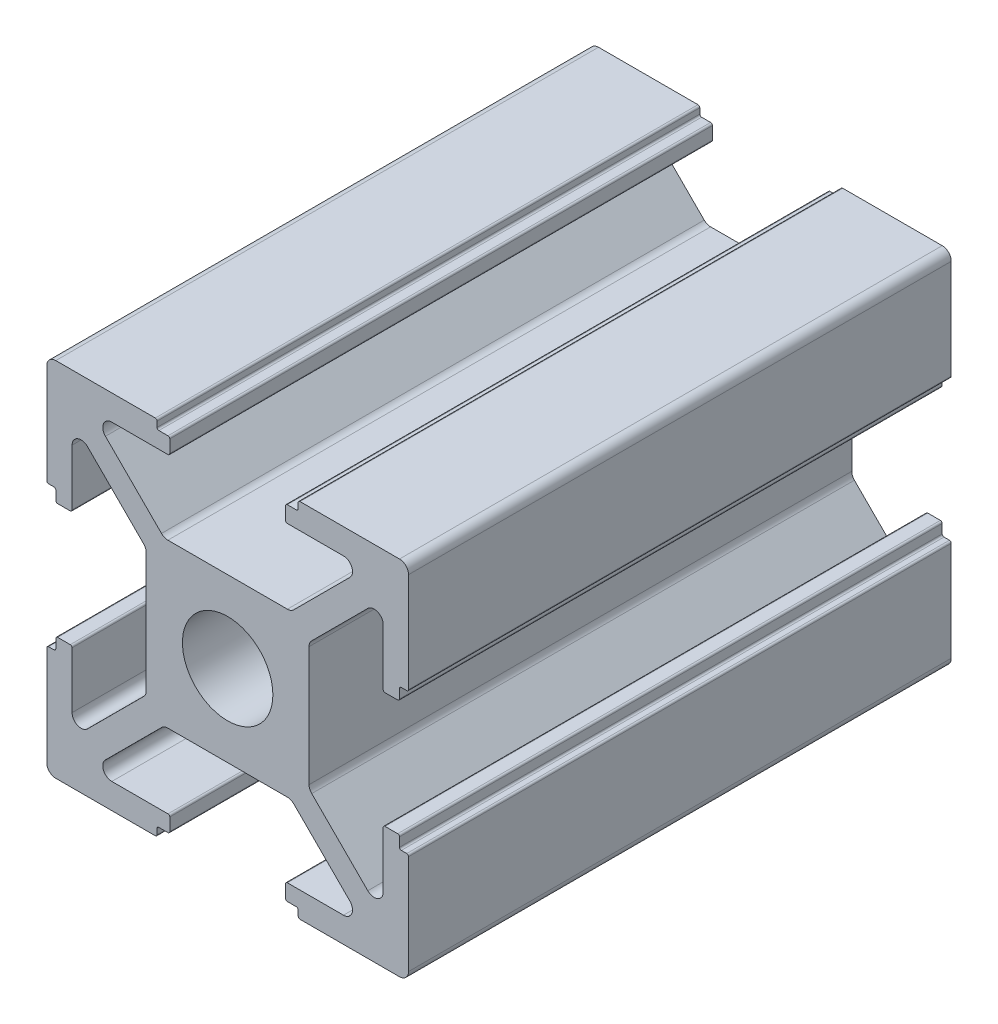
SolidWorks part; units mm, degrees
material "6061 Alaşım"
ref_plane "Ön Düzlem" through (0, 0, 0) normal (0, 0, 1) x (1, 0, 0)
ref_plane "Üst Düzlem" through (0, 0, 0) normal (0, 1, 0) x (1, 0, 0)
ref_plane "Sağ Düzlem" through (0, 0, 0) normal (1, 0, 0) x (0, 0, -1)
sketch "Çizim1" plane through (0, 0, 0) normal (0, 0, 1) x (1, 0, 0)
  line L0 (0, 0) -> (10, 10) construction
  line L1 (10, -10) -> (-10, -10) construction
  line L2 (10, -10) -> (10, 10) construction
  line L3 (10, 10) -> (-10, 10) construction
  line L4 (-10, -10) -> (-10, 10) construction
  line L5 (0, 10) -> (0, -10) construction
  line L6 (10, 0) -> (-10, 0) construction
  line L7 (4.5, 3.5101) -> (10, 9.0101) construction
  line L8 (3.5101, 4.5) -> (9.0101, 10) construction
  line L9 (10, 3.2) -> (8.6, 3.2) construction
  line L10 (8.6, 3.3) -> (8.6, 6.4029)
  line L11 (6.4029, 8.6) -> (3.3, 8.6)
  line L12 (3.2, 8.6) -> (3.2, 10) construction
  line L13 (3.6565, 4.6464) -> (6.7565, 7.7464)
  line L14 (7.7464, 6.7565) -> (4.6464, 3.6565)
  line L15 (3.2, 10) -> (9.5, 10) construction
  line L16 (10, 9.5) -> (10, 3.2) construction
  line L17 (4.5, 3.3029) -> (4.5, 0)
  line L18 (3.3029, 4.5) -> (0, 4.5)
  line L19 (3.3, 9.5) -> (3.8, 9.5)
  line L20 (3.9, 9.6) -> (3.9, 9.9)
  line L21 (3.2, 9.4) -> (3.2, 8.7)
  line L22 (4, 10) -> (9.5, 10)
  line L23 (9.5, 3.3) -> (9.5, 3.8)
  line L24 (9.6, 3.9) -> (9.9, 3.9)
  line L25 (8.7, 3.2) -> (9.4, 3.2)
  line L26 (10, 4) -> (10, 9.5)
  line L27 (0, 0) -> (10, -10) construction
  line L28 (3.3029, -4.5) -> (0, -4.5)
  line L29 (6.7565, -7.7464) -> (3.6565, -4.6464)
  line L30 (3.3, -8.6) -> (6.4029, -8.6)
  line L31 (3.2, -8.7) -> (3.2, -9.4)
  line L32 (3.3, -9.5) -> (3.8, -9.5)
  line L33 (3.9, -9.6) -> (3.9, -9.9)
  line L34 (4, -10) -> (9.5, -10)
  line L35 (10, -4) -> (10, -9.5)
  line L36 (9.6, -3.9) -> (9.9, -3.9)
  line L37 (9.5, -3.3) -> (9.5, -3.8)
  line L38 (9.4, -3.2) -> (8.7, -3.2)
  line L39 (8.6, -6.4029) -> (8.6, -3.3)
  line L40 (4.6464, -3.6565) -> (7.7464, -6.7565)
  line L41 (4.5, -3.3029) -> (4.5, 0)
  line L42 (0, 0) -> (-10, -10) construction
  line L43 (-4.5, -3.3029) -> (-4.5, 0)
  line L44 (-7.7464, -6.7565) -> (-4.6464, -3.6565)
  line L45 (-8.6, -3.3) -> (-8.6, -6.4029)
  line L46 (-8.7, -3.2) -> (-9.4, -3.2)
  line L47 (-9.5, -3.3) -> (-9.5, -3.8)
  line L48 (-9.6, -3.9) -> (-9.9, -3.9)
  line L49 (-10, -4) -> (-10, -9.5)
  line L50 (-4, -10) -> (-9.5, -10)
  line L51 (-3.9, -9.6) -> (-3.9, -9.9)
  line L52 (-3.3, -9.5) -> (-3.8, -9.5)
  line L53 (-3.2, -9.4) -> (-3.2, -8.7)
  line L54 (-6.4029, -8.6) -> (-3.3, -8.6)
  line L55 (-3.6565, -4.6464) -> (-6.7565, -7.7464)
  line L56 (-3.3029, -4.5) -> (0, -4.5)
  line L57 (0, 0) -> (-10, 10) construction
  line L58 (-3.3029, 4.5) -> (0, 4.5)
  line L59 (-6.7565, 7.7464) -> (-3.6565, 4.6464)
  line L60 (-3.3, 8.6) -> (-6.4029, 8.6)
  line L61 (-3.2, 8.7) -> (-3.2, 9.4)
  line L62 (-3.3, 9.5) -> (-3.8, 9.5)
  line L63 (-3.9, 9.6) -> (-3.9, 9.9)
  line L64 (-4, 10) -> (-9.5, 10)
  line L65 (-10, 4) -> (-10, 9.5)
  line L66 (-9.6, 3.9) -> (-9.9, 3.9)
  line L67 (-9.5, 3.3) -> (-9.5, 3.8)
  line L68 (-9.4, 3.2) -> (-8.7, 3.2)
  line L69 (-8.6, 6.4029) -> (-8.6, 3.3)
  line L70 (-4.6464, 3.6565) -> (-7.7464, 6.7565)
  line L71 (-4.5, 3.3029) -> (-4.5, 0)
  circle A0 centre (0, 0) radius 2.5
  arc A1 (10, 9.5) -> (9.5, 10) centre (9.5, 9.5) ccw
  arc A2 (4.5, 3.3029) -> (4.6464, 3.6565) centre (5, 3.3029) cw
  arc A3 (3.6565, 4.6464) -> (3.3029, 4.5) centre (3.3029, 5) cw
  arc A4 (8.6, 6.4029) -> (7.7464, 6.7565) centre (8.1, 6.4029) ccw
  arc A5 (6.4029, 8.6) -> (6.7565, 7.7464) centre (6.4029, 8.1) cw
  arc A6 (9.5, 3.8) -> (9.6, 3.9) centre (9.6, 3.8) cw
  arc A7 (9.9, 3.9) -> (10, 4) centre (9.9, 4) ccw
  arc A8 (8.7, 3.2) -> (8.6, 3.3) centre (8.7, 3.3) cw
  arc A9 (9.5, 3.3) -> (9.4, 3.2) centre (9.4, 3.3) cw
  arc A10 (3.3, 8.6) -> (3.2, 8.7) centre (3.3, 8.7) cw
  arc A11 (3.8, 9.5) -> (3.9, 9.6) centre (3.8, 9.6) ccw
  arc A12 (3.9, 9.9) -> (4, 10) centre (4, 9.9) cw
  arc A13 (3.3, 9.5) -> (3.2, 9.4) centre (3.3, 9.4) ccw
  arc A14 (3.3029, -4.5) -> (3.6565, -4.6464) centre (3.3029, -5) cw
  arc A15 (6.4029, -8.6) -> (6.7565, -7.7464) centre (6.4029, -8.1) ccw
  arc A16 (3.2, -8.7) -> (3.3, -8.6) centre (3.3, -8.7) cw
  arc A17 (3.3, -9.5) -> (3.2, -9.4) centre (3.3, -9.4) cw
  arc A18 (3.8, -9.5) -> (3.9, -9.6) centre (3.8, -9.6) cw
  arc A19 (3.9, -9.9) -> (4, -10) centre (4, -9.9) ccw
  arc A20 (9.5, -10) -> (10, -9.5) centre (9.5, -9.5) ccw
  arc A21 (9.9, -3.9) -> (10, -4) centre (9.9, -4) cw
  arc A22 (9.5, -3.8) -> (9.6, -3.9) centre (9.6, -3.8) ccw
  arc A23 (9.5, -3.3) -> (9.4, -3.2) centre (9.4, -3.3) ccw
  arc A24 (8.6, -3.3) -> (8.7, -3.2) centre (8.7, -3.3) cw
  arc A25 (8.6, -6.4029) -> (7.7464, -6.7565) centre (8.1, -6.4029) cw
  arc A26 (4.6464, -3.6565) -> (4.5, -3.3029) centre (5, -3.3029) cw
  arc A27 (-4.5, -3.3029) -> (-4.6464, -3.6565) centre (-5, -3.3029) cw
  arc A28 (-8.6, -6.4029) -> (-7.7464, -6.7565) centre (-8.1, -6.4029) ccw
  arc A29 (-8.7, -3.2) -> (-8.6, -3.3) centre (-8.7, -3.3) cw
  arc A30 (-9.5, -3.3) -> (-9.4, -3.2) centre (-9.4, -3.3) cw
  arc A31 (-9.5, -3.8) -> (-9.6, -3.9) centre (-9.6, -3.8) cw
  arc A32 (-9.9, -3.9) -> (-10, -4) centre (-9.9, -4) ccw
  arc A33 (-10, -9.5) -> (-9.5, -10) centre (-9.5, -9.5) ccw
  arc A34 (-3.9, -9.9) -> (-4, -10) centre (-4, -9.9) cw
  arc A35 (-3.8, -9.5) -> (-3.9, -9.6) centre (-3.8, -9.6) ccw
  arc A36 (-3.3, -9.5) -> (-3.2, -9.4) centre (-3.3, -9.4) ccw
  arc A37 (-3.3, -8.6) -> (-3.2, -8.7) centre (-3.3, -8.7) cw
  arc A38 (-6.4029, -8.6) -> (-6.7565, -7.7464) centre (-6.4029, -8.1) cw
  arc A39 (-3.6565, -4.6464) -> (-3.3029, -4.5) centre (-3.3029, -5) cw
  arc A40 (-3.3029, 4.5) -> (-3.6565, 4.6464) centre (-3.3029, 5) cw
  arc A41 (-6.4029, 8.6) -> (-6.7565, 7.7464) centre (-6.4029, 8.1) ccw
  arc A42 (-3.2, 8.7) -> (-3.3, 8.6) centre (-3.3, 8.7) cw
  arc A43 (-3.3, 9.5) -> (-3.2, 9.4) centre (-3.3, 9.4) cw
  arc A44 (-3.8, 9.5) -> (-3.9, 9.6) centre (-3.8, 9.6) cw
  arc A45 (-3.9, 9.9) -> (-4, 10) centre (-4, 9.9) ccw
  arc A46 (-9.5, 10) -> (-10, 9.5) centre (-9.5, 9.5) ccw
  arc A47 (-9.9, 3.9) -> (-10, 4) centre (-9.9, 4) cw
  arc A48 (-9.5, 3.8) -> (-9.6, 3.9) centre (-9.6, 3.8) ccw
  arc A49 (-9.5, 3.3) -> (-9.4, 3.2) centre (-9.4, 3.3) ccw
  arc A50 (-8.6, 3.3) -> (-8.7, 3.2) centre (-8.7, 3.3) cw
  arc A51 (-8.6, 6.4029) -> (-7.7464, 6.7565) centre (-8.1, 6.4029) cw
  arc A52 (-4.6464, 3.6565) -> (-4.5, 3.3029) centre (-5, 3.3029) cw
  point P0 (0, 0)
  point P32 (8.6, 7.6101)
  point P35 (7.6101, 8.6)
  point P41 (9.5, 3.9)
  point P44 (10, 3.9)
  point P50 (9.5, 3.2)
  point P62 (3.9, 9.5)
  point P65 (3.9, 10)
  point P68 (3.2, 9.5)
  point P198 (0, 0)
  dimension "D3" = 5
  dimension "D10" = 0.5
  dimension "D13" = 0.1
  dimension "D1" = 20
  dimension "D2" = 20
  dimension "D4" = 0.7
  dimension "D5" = 3.2
  dimension "D6" = 2.8
  dimension "D7" = 3.2
  dimension "D8" = 1.4
  dimension "D9" = 5.5
  dimension "D11" = 0.7
  dimension "D12" = 0.7
  dimension "D14" = 4
extrude "Yükseklik-Ekstrüzyon1" add sketch "Çizim1" along normal blind 30 contours L70 A52 L71 L43 A27 L44 A28 L45 A29 L46 A30 L47 A31 L48 A32 L49 A33 L50 A34 L51 A35 L52 A36 L53 A37 L54 A38 L55 A39 L56 L28 A14 L29 A15 L30 A16 L31 A17 L32 A18 L33 A19 L34 A20 L35 A21 L36 A22 L37 A23 L38
